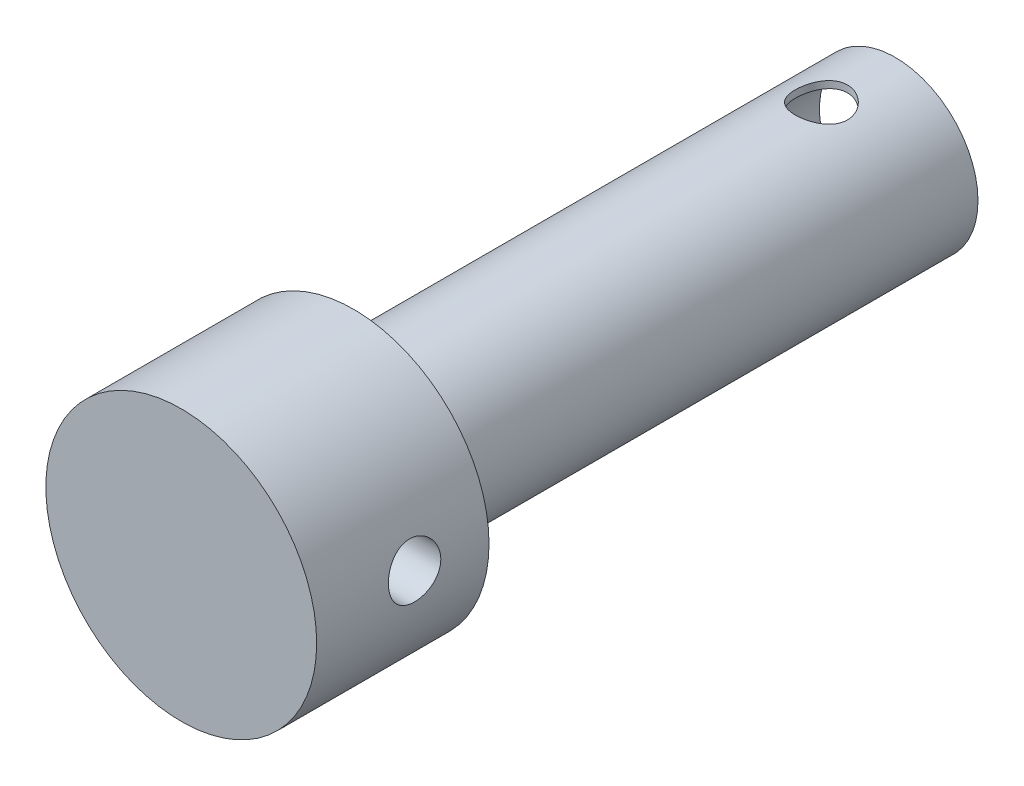
SolidWorks part; units mm, degrees
ref_plane "Front" through (0, 0, 0) normal (0, 0, 1) x (1, 0, 0)
ref_plane "Top" through (0, 0, 0) normal (0, 1, 0) x (1, 0, 0)
ref_plane "Right" through (0, 0, 0) normal (1, 0, 0) x (0, 0, -1)
sketch "Sketch1" plane through (0, 0, 0) normal (0, 0, 1) x (1, 0, 0)
  circle A0 centre (0, 0) radius 10.668
  circle A1 centre (0, 0) radius 9.779
  dimension "D1" = 21.336
  dimension "D2" = 19.558
extrude "Boss-Extrude1" add sketch "Sketch1" along normal blind 88.9
sketch "Sketch4" plane through (0, 0, 88.9) normal (0, 0, 1) x (1, 0, 0)
  circle A0 centre (0, 0) radius 17.4625
extrude "Boss-Extrude2" add sketch "Sketch4" against normal blind 19.05
sketch "Sketch5" plane through (0, 0, 0) normal (1, 0, 0) x (0, 0, -1)
  line L1 (-88.9, 17.4625) -> (-88.9, -17.4625) construction
  line L2 (-69.85, 17.4625) -> (-88.9, 17.4625) construction
  circle A0 centre (-79.375, 1.5875) radius 3.3655
  dimension "D1" = 6.731
  dimension "D2" = 9.525
  dimension "D3" = 15.875
extrude "Cut-Extrude1" cut sketch "Sketch5" against normal through all both and the other way through all
sketch "Sketch7" plane through (0, 0, 0) normal (0, 1, 0) x (1, 0, 0)
  line L1 (9.779, 0) -> (-9.779, 0) construction
  line L3 (10.668, 0) -> (-10.668, 0) construction
  circle A0 centre (0, -9.525) radius 3.3655
  dimension "D1" = 9.525
  dimension "D2" = 9.525
  dimension "D3" = 9.525
  dimension "D4" = 9.525
extrude "Cut-Extrude2" cut sketch "Sketch7" against normal through all both and the other way through all
sketch "Sketch8" plane through (0, 0, 88.9) normal (0, 0, 1) x (1, 0, 0)
  circle A0 centre (0, 0) radius 9.652
extrude "Cut-Extrude3" cut sketch "Sketch8" against normal through all
sketch "Sketch9" plane through (0, 0, 88.9) normal (0, 0, 1) x (1, 0, 0)
  circle A0 centre (0, 0) radius 17.4625
extrude "Boss-Extrude3" add sketch "Sketch9" along normal blind 3.175
